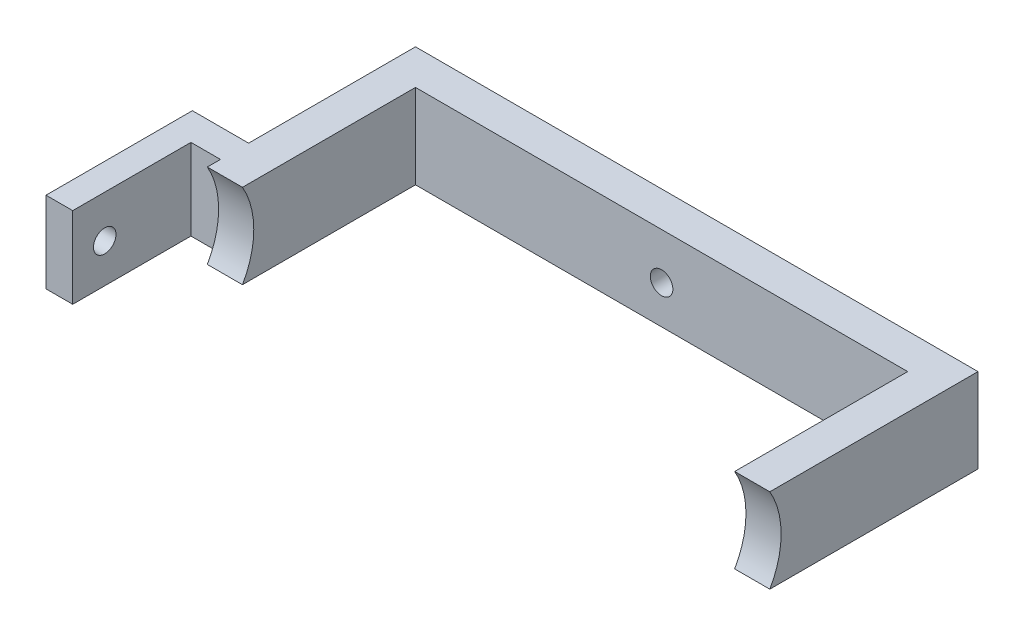
SolidWorks part; units mm, degrees
ref_plane "Front Plane" through (0, 0, 0) normal (0, 0, 1) x (1, 0, 0)
ref_plane "Top Plane" through (0, 0, 0) normal (0, 1, 0) x (1, 0, 0)
ref_plane "Right Plane" through (0, 0, 0) normal (1, 0, 0) x (0, 0, -1)
sketch "Sketch1" plane through (0, 0, 0) normal (0, 1, 0) x (1, 0, 0)
  line L1 (-100, 100) -> (100, 100)
  line L2 (-100, 100) -> (-100, -100)
  line L3 (-100, -100) -> (100, -100)
  line L4 (100, 100) -> (100, -100)
  line L5 (-100, 100) -> (100, -100) construction
  line L6 (-100, -100) -> (100, 100) construction
  point P0 (0, 0)
extrude "Boss-Extrude1" add sketch "Sketch1" along normal blind 30
sketch "Sketch4" plane through (0, 30, 0) normal (0, 1, 0) x (1, 0, 0)
  line L1 (-87.5, -87.5) -> (87.5, -87.5)
  line L2 (-87.5, -87.5) -> (-87.5, 87.5)
  line L3 (-87.5, 87.5) -> (87.5, 87.5)
  line L4 (87.5, -87.5) -> (87.5, 87.5)
  line L5 (-87.5, -87.5) -> (87.5, 87.5) construction
  line L6 (-87.5, 87.5) -> (87.5, -87.5) construction
  point P0 (0, 0)
extrude "Cut-Extrude1" cut sketch "Sketch4" against normal blind 30
sketch "Sketch7" plane through (-100, 0, 0) normal (-1, 0, 0) x (0, 0, 1)
  circle A0 centre (0, 15) radius 4
extrude "Cut-Extrude2" cut sketch "Sketch7" against normal blind 210
sketch "Sketch10" plane through (-100, 0, 0) normal (-1, 0, 0) x (0, 0, 1)
  line L0 (-8.6266, 30) -> (-8.6266, 0)
  line L1 (-100, 30) -> (100, 30) construction
  line L2 (-100, 0) -> (100, 0) construction
  line L3 (-8.6266, 0) -> (-14.6668, 0)
  line L4 (-14.6668, 0) -> (-14.6668, 30)
  line L5 (-14.6668, 30) -> (-8.6266, 30)
extrude "Boss-Extrude2" add sketch "Sketch10" along normal blind 20
sketch "Sketch11" plane through (0, 0, -8.6266) normal (0, 0, 1) x (1, 0, 0)
  line L0 (-120, 0) -> (-120, 30)
  line L1 (-120, 30) -> (-110, 30)
  line L2 (-120, 30) -> (-100, 30) construction
  line L3 (-110, 30) -> (-110, 0)
  line L4 (-120, 0) -> (-100, 0) construction
  line L5 (-110, 0) -> (-120, 0)
extrude "Boss-Extrude3" add sketch "Sketch11" along normal blind 20
sketch "Sketch12" plane through (100, 0, 0) normal (1, 0, 0) x (0, 0, -1)
  circle A0 centre (0, 15) radius 4
extrude "Cut-Extrude3" cut sketch "Sketch12" against normal blind 231
sketch "Sketch13" plane through (0, 30, 0) normal (0, 1, 0) x (1, 0, 0)
  circle A0 centre (-93.6945, -93.0455) radius 4
extrude "Cut-Extrude5" cut sketch "Sketch13" against normal blind 231
sketch "Sketch14" plane through (0, 0, 100) normal (0, 0, 1) x (1, 0, 0)
  circle A0 centre (0, 13.6147) radius 4
extrude "Cut-Extrude6" cut sketch "Sketch14" against normal blind 250.5
sketch "Sketch15" plane through (100, 0, 0) normal (1, 0, 0) x (0, 0, -1)
  circle A0 centre (0, 15) radius 30
  circle A1 centre (0, 15) radius 22
extrude "Boss-Extrude5" add sketch "Sketch15" against normal blind 201
sketch "Sketch17" plane through (100, 0, 0) normal (1, 0, 0) x (0, 0, -1)
  circle A0 centre (0.0744, 15.1008) radius 22
extrude "Cut-Extrude7" cut sketch "Sketch17" against normal blind 201
sketch "Sketch18" plane through (87.5, 0, 0) normal (-1, 0, 0) x (0, 0, 1)
  line L1 (-87.5, 0) -> (87.5, 0)
  line L2 (-87.5, 0) -> (-87.5, 30)
  line L3 (-87.5, 30) -> (87.5, 30)
  line L4 (87.5, 0) -> (87.5, 30)
sketch "Sketch21" plane through (0, 0, -14.6668) normal (0, 0, -1) x (-1, 0, 0)
  line L0 (120, 30) -> (120, 0) construction
  line L1 (120, 1.1441) -> (110.5, 1.1441)
  line L2 (120, 1.1441) -> (120, 30)
  line L3 (120, 30) -> (110.5, 30)
  line L4 (110.5, 1.1441) -> (110.5, 30)
  line L5 (120, 30) -> (101, 30) construction
extrude "Boss-Extrude6" add sketch "Sketch21" along normal blind 26
sketch "Sketch22" plane through (0, 30, 0) normal (0, 1, 0) x (1, 0, 0)
  line L1 (-110.5, 14.6668) -> (-101, 14.6668)
  line L2 (-110.5, 14.6668) -> (-110.5, 8.6266)
  line L3 (-110.5, 8.6266) -> (-101, 8.6266)
  line L4 (-101, 14.6668) -> (-101, 8.6266)
extrude "Cut-Extrude10" cut sketch "Sketch22" against normal blind 49
sketch "Sketch23" plane through (-110.5, 0, 0) normal (1, 0, 0) x (0, 0, -1)
  line L0 (40.6668, 1.1441) -> (14.6668, 1.1441) construction
  line L1 (40.6668, 30) -> (30.6579, 30)
  line L2 (40.6668, 30) -> (40.6668, 1.1441)
  line L3 (40.6668, 1.1441) -> (30.6579, 1.1441)
  line L4 (30.6579, 30) -> (30.6579, 1.1441)
extrude "Boss-Extrude7" add sketch "Sketch23" along normal blind 21
sketch "Sketch24" plane through (0, 0, -14.6668) normal (0, 0, -1) x (-1, 0, 0)
  line L1 (120, 0) -> (110.5, 0)
  line L2 (120, 0) -> (120, 1.1441)
  line L3 (120, 1.1441) -> (110.5, 1.1441)
  line L4 (110.5, 0) -> (110.5, 1.1441)
extrude "Cut-Extrude11" cut sketch "Sketch24" against normal blind 27
sketch "Sketch26" plane through (0, 0, 0) normal (0, -1, 0) x (1, 0, 0)
  line L1 (-110.5, -8.6266) -> (-109.9986, -8.6266)
  line L2 (-110.5, -8.6266) -> (-110.5, 12.267)
  line L3 (-110.5, 12.267) -> (-109.9986, 12.267)
  line L4 (-109.9986, -8.6266) -> (-109.9986, 12.267)
extrude "Cut-Extrude12" cut sketch "Sketch26" against normal blind 35
sketch "Sketch27" plane through (-87.5, 0, 0) normal (1, 0, 0) x (0, 0, -1)
  circle A0 centre (-31.9164, 15.3761) radius 49.1928
extrude "Cut-Extrude13" cut sketch "Sketch27" along normal blind 175
sketch "Sketch28" plane through (-87.5, 0, 0) normal (1, 0, 0) x (0, 0, -1)
  circle A0 centre (37.7624, 15.4944) radius 41.209
extrude "Cut-Extrude14" cut sketch "Sketch28" along normal blind 175
sketch "Sketch29" plane through (100, 0, 0) normal (1, 0, 0) x (0, 0, -1)
  circle A0 centre (0, 15) radius 30
sketch "Sketch30" plane through (100, 0, 0) normal (1, 0, 0) x (0, 0, -1)
  line L0 (25.9808, 30) -> (100, 30) construction
  arc A0 (25.9808, 0) -> (25.9808, 30) centre (0, 15) ccw
extrude "Cut-Extrude15" cut sketch "Sketch30" against normal blind 210 and the other way through all
